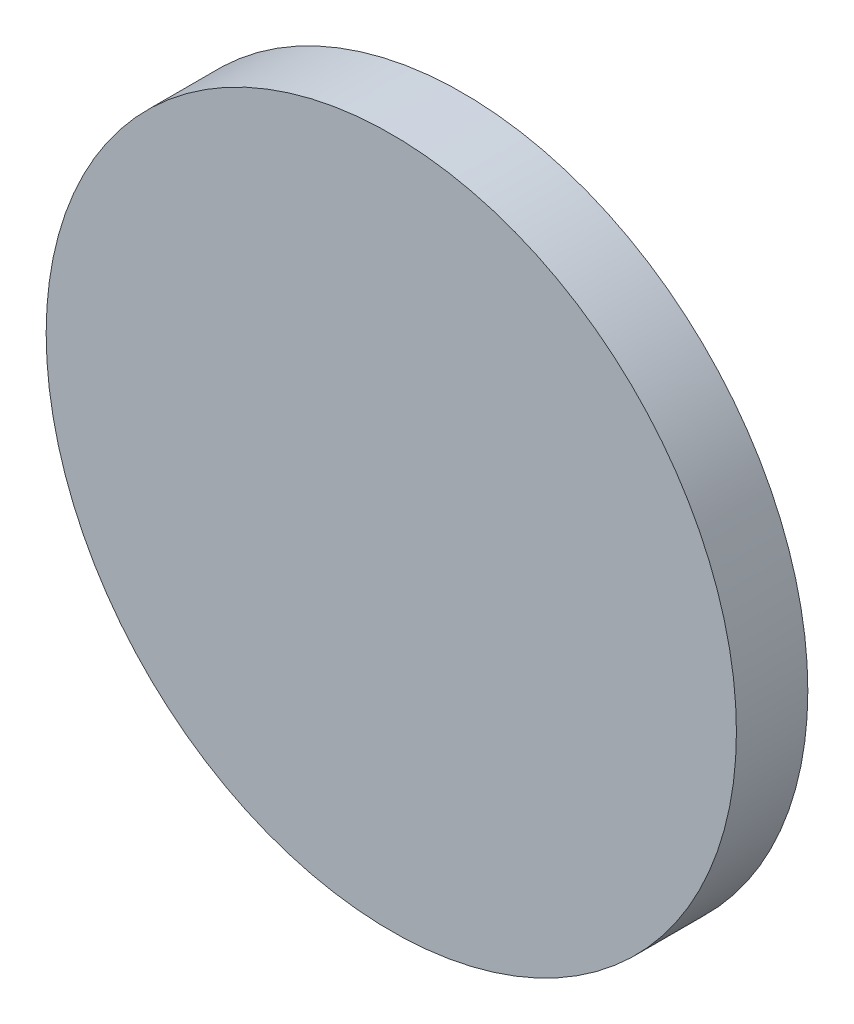
SolidWorks part; units mm, degrees
material "PE1000 Высокой плотности"
ref_plane "Спереди" through (0, 0, 0) normal (0, 0, 1) x (1, 0, 0)
ref_plane "Сверху" through (0, 0, 0) normal (0, 1, 0) x (1, 0, 0)
ref_plane "Справа" through (0, 0, 0) normal (1, 0, 0) x (0, 0, -1)
sketch "Эскиз1" plane through (0, 0, 0) normal (0, 0, 1) x (1, 0, 0)
  circle A0 centre (0, 0) radius 14.5
  dimension "D1" = 29
extrude "Бобышка-Вытянуть1" add sketch "Эскиз1" along normal blind 3
